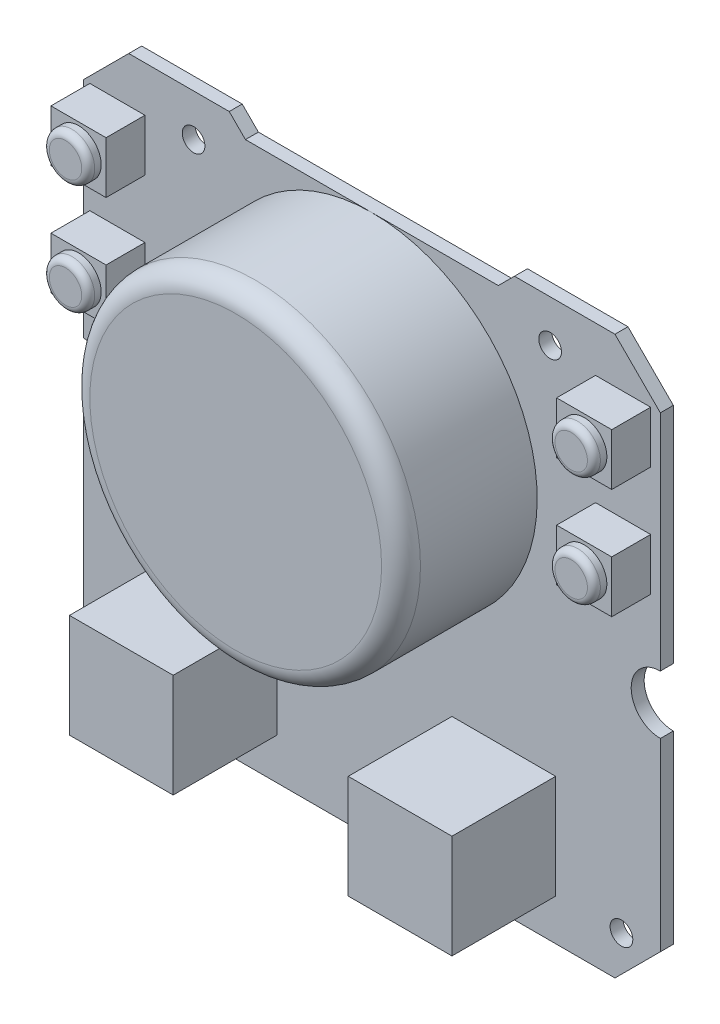
SolidWorks part; units mm, degrees
ref_plane "Front" through (0, 0, 0) normal (0, 0, 1) x (1, 0, 0)
ref_plane "Top" through (0, 0, 0) normal (0, 1, 0) x (1, 0, 0)
ref_plane "Right" through (0, 0, 0) normal (1, 0, 0) x (0, 0, -1)
sketch "Sketch1" plane through (0, 0, 0) normal (0, 0, 1) x (1, 0, 0)
  line L0 (44.5, 43) -> (-44.5, -43) construction
  line L1 (37.5, 43) -> (-37.5, 43)
  line L2 (44.5, 36) -> (44.5, -36)
  line L3 (37.5, -43) -> (-37.5, -43)
  line L4 (-44.5, 36) -> (-44.5, -36)
  line L5 (-37.5, 43) -> (-44.5, 36)
  line L6 (37.5, 43) -> (44.5, 36)
  line L7 (44.5, -36) -> (37.5, -43)
  line L8 (-44.5, -36) -> (-37.5, -43)
  line L9 (-22, 43) -> (-19.5, 40.5)
  line L10 (-19.5, 40.5) -> (19.5, 40.5)
  line L11 (19.5, 40.5) -> (22, 43)
  line L12 (0, 40.5) -> (0, 43) construction
  arc A0 (44.5, 1.5) -> (44.5, -7.5) centre (44.5, -3) ccw
  arc A1 (-44.5, -7.5) -> (-44.5, 1.5) centre (-44.5, -3) ccw
  point P2 (44.5, -43)
  point P3 (-44.5, 43)
  point P25 (19.5675, 40.5)
  dimension "D3" = 9
  dimension "D1" = 86
  dimension "D2" = 89
  dimension "D4" = 40
  dimension "D5" = 2.5
  dimension "D6" = 135
  dimension "D11" = 44
extrude "Boss-Extrude1" add sketch "Sketch1" against normal blind 2 contours A1 L4 L8 L3 L7 L2 A0 L6 L1 L11 L10 L9 L5
sketch "Sketch2" plane through (0, 0, 0) normal (0, 0, 1) x (1, 0, 0)
  line L0 (-44.5, 36) -> (-44.5, 1.5) construction
  line L1 (-43.5, 36) -> (-35, 36)
  line L2 (-43.5, 36) -> (-43.5, 28)
  line L3 (-43.5, 28) -> (-35, 28)
  line L4 (-35, 36) -> (-35, 28)
  line L5 (-22, 43) -> (-37.5, 43) construction
  line L6 (34.5, 28) -> (43, 28)
  line L7 (43, 36) -> (43, 28)
  line L8 (34.5, 36) -> (34.5, 28)
  line L9 (34.5, 36) -> (43, 36)
  line L10 (34.5, 11) -> (43, 11)
  line L11 (43, 19) -> (43, 11)
  line L12 (34.5, 19) -> (34.5, 11)
  line L13 (34.5, 19) -> (43, 19)
  line L14 (-43.5, 11) -> (-35, 11)
  line L15 (-35, 19) -> (-35, 11)
  line L16 (-43.5, 19) -> (-43.5, 11)
  line L17 (-43.5, 19) -> (-35, 19)
  dimension "D1" = 8
  dimension "D2" = 8.5
  dimension "D3" = 1
  dimension "D4" = 15
  dimension "D5" = 2
  dimension "D6" = 2
extrude "Boss-Extrude2" add sketch "Sketch2" along normal blind 6
sketch "Sketch3" plane through (0, 0, 6) normal (0, 0, 1) x (1, 0, 0)
  line L0 (-35, 32) -> (-43.5, 32) construction
  line L1 (-35, 28) -> (-35, 36) construction
  line L2 (-43.5, 36) -> (-43.5, 28) construction
  circle A0 centre (-39.25, 32) radius 3.5
  circle A1 centre (38.75, 32) radius 3.5
  circle A2 centre (38.75, 15) radius 3.5
  circle A3 centre (-39.25, 15) radius 3.5
  dimension "D1" = 7
  dimension "D2" = 2
  dimension "D3" = 2
extrude "Boss-Extrude3" add sketch "Sketch3" along normal blind 2
fillet "Fillet1" radius 1 4 edges at (42.25, 32, 8) (42.25, 15, 8) (-35.75, 15, 8) (-35.75, 32, 8)
sketch "Sketch4" plane through (0, 0, 0) normal (0, 0, 1) x (1, 0, 0)
  line L1 (-19.5, 40.5) -> (19.5, 40.5) construction
  circle A0 centre (0, 15) radius 25.5
  dimension "D1" = 51
extrude "Boss-Extrude4" add sketch "Sketch4" along normal blind 21
fillet "Fillet2" radius 3 1 edges at (25.5, 15, 21)
sketch "Sketch6" plane through (0, 0, 0) normal (0, 0, 1) x (1, 0, 0)
  line L0 (12.3553, -20.6309) -> (12.3553, -36.6309)
  line L1 (-30.6447, -20.6309) -> (-14.6447, -20.6309)
  line L2 (-30.6447, -20.6309) -> (-30.6447, -36.6309)
  line L3 (-30.6447, -36.6309) -> (-14.6447, -36.6309)
  line L4 (-14.6447, -20.6309) -> (-14.6447, -36.6309)
  line L5 (12.3553, -20.6309) -> (28.3553, -20.6309)
  line L6 (12.3553, -36.6309) -> (28.3553, -36.6309)
  line L7 (28.3553, -20.6309) -> (28.3553, -36.6309)
  dimension "D1" = 16
  dimension "D2" = 2
extrude "Boss-Extrude5" add sketch "Sketch6" along normal blind 16
sketch "Sketch7" plane through (0, 0, 0) normal (0, 0, 1) x (1, 0, 0)
  line L0 (-44.5, 36) -> (-44.5, 1.5) construction
  line L1 (-22, 43) -> (-37.5, 43) construction
  line L2 (44.5, 36) -> (44.5, 1.5) construction
  line L3 (-44.5, -7.5) -> (-44.5, -36) construction
  line L4 (37.5, -43) -> (-37.5, -43) construction
  circle A0 centre (-27.5, 36.5) radius 1.75
  circle A1 centre (27.5, 36.5) radius 1.75
  circle A2 centre (-38, -36.5) radius 1.75
  circle A3 centre (38.5, -36.5) radius 1.75
  point P18 (38.4815, -34.8162)
  dimension "D1" = 3.5
  dimension "D3" = 17
  dimension "D4" = 6.5
  dimension "D5" = 17
  dimension "D6" = 76.5
  dimension "D7" = 6.5
  dimension "D8" = 6.5
  dimension "D2" = 2
extrude "Cut-Extrude1" cut sketch "Sketch7" against normal through all and the other way through all
equation "\"6.5mmm\"=6.07024"
equation "\"D8@Sketch7\"=\"D7@Sketch7\""
